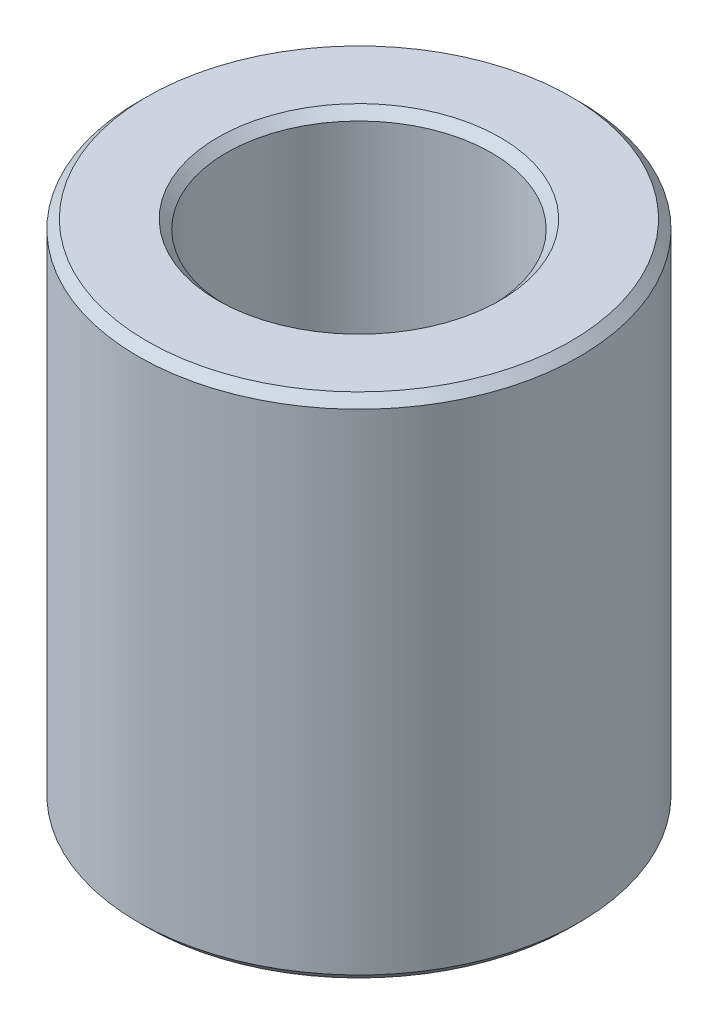
SolidWorks part; units mm, degrees
ref_plane "Front Plane" through (0, 0, 0) normal (0, 0, 1) x (1, 0, 0)
ref_plane "Top Plane" through (0, 0, 0) normal (0, 1, 0) x (1, 0, 0)
ref_plane "Right Plane" through (0, 0, 0) normal (1, 0, 0) x (0, 0, -1)
sketch "Sketch1" plane through (0, 0, 0) normal (0, 1, 0) x (1, 0, 0)
  circle A0 centre (0, 0) radius 3
  circle A1 centre (0, 0) radius 5
  dimension "D1" = 6
  dimension "D2" = 2
extrude "Boss-Extrude1" add sketch "Sketch1" along normal blind 11.5
chamfer "Chamfer1" distance 0.2 angle 45 4 edges at (0, 11.5, 3) (0, 11.5, 5) (0, 0, 3) (0, 0, 5)
